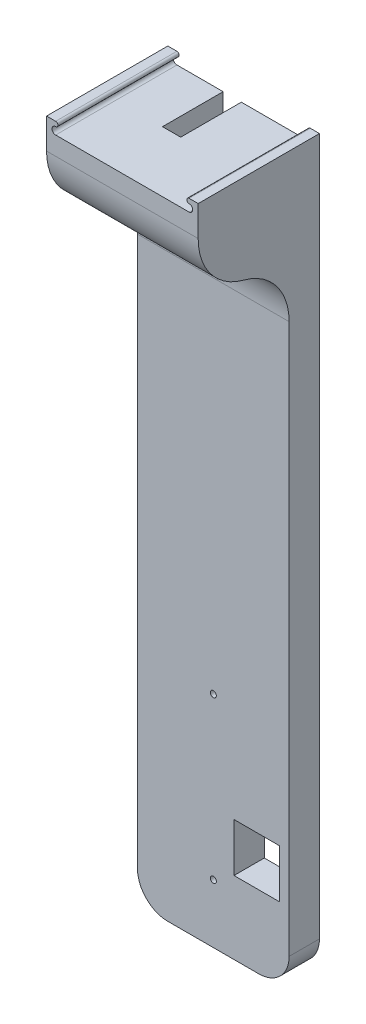
SolidWorks part; units mm, degrees
ref_plane "Přední rovina" through (0, 0, 0) normal (0, 0, 1) x (1, 0, 0)
ref_plane "Horní rovina" through (0, 0, 0) normal (0, 1, 0) x (1, 0, 0)
ref_plane "Pravá rovina" through (0, 0, 0) normal (1, 0, 0) x (0, 0, -1)
sketch "Skica1" plane through (0, 0, 0) normal (0, 0, 1) x (1, 0, 0)
  line L1 (0, 0) -> (25, 0)
  line L2 (0, 0) -> (0, 120)
  line L3 (0, 120) -> (25, 120)
  line L4 (25, 0) -> (25, 120)
  dimension "D1" = 120
  dimension "D2" = 25
extrude "Přidat vysunutím1" add sketch "Skica1" along normal blind 5
sketch "Skica2" plane through (0, 0, 0) normal (0, 0, -1) x (-1, 0, 0)
  line L0 (0, 120) -> (0, 0) construction
  line L1 (-25, 120) -> (0, 120)
  line L2 (-25, 120) -> (-25, 105)
  line L3 (-25, 105) -> (0, 105)
  line L4 (0, 120) -> (0, 105)
  dimension "D1" = 15
extrude "Přidat vysunutím2" add sketch "Skica2" against normal blind 20
fillet "Zaoblit5" radius 5 1 edges at (25, 0, 2.5)
fillet "Zaoblit6" radius 5 1 edges at (0, 0, 2.5)
sketch "Skica3" plane through (0, 0, 20) normal (0, 0, 1) x (1, 0, 0)
  line L0 (1.5, 118.04) -> (23.5, 118.04)
  line L1 (0, 120) -> (25, 120) construction
  line L4 (1.5, 120) -> (23.5, 120)
  line L5 (0, 105) -> (0, 120) construction
  line L6 (25, 120) -> (25, 105) construction
  arc A0 (23.5, 118.04) -> (23.5, 119.24) centre (23.5, 118.64) ccw
  arc A1 (23.5, 119.24) -> (23.5, 120) centre (23.5, 119.62) cw
  arc A2 (1.5, 118.04) -> (1.5, 119.24) centre (1.5, 118.64) cw
  arc A3 (1.5, 119.24) -> (1.5, 120) centre (1.5, 119.62) ccw
  dimension "D1" = 0.6
  dimension "D2" = 0.6
  dimension "D3" = 0.38
  dimension "D4" = 0.38
  dimension "D5" = 1.5
  dimension "D6" = 1.5
  dimension "D7" = 1.96
extrude "Odebrat vysunutím2" cut sketch "Skica3" against normal blind 20
fillet "Zaoblit7" radius 10 1 edges at (12.5, 105, 20)
fillet "Zaoblit8" radius 10 1 edges at (12.5, 105, 5)
sketch "Skica4" plane through (0, 118.04, 0) normal (0, 1, 0) x (1, 0, 0)
  line L0 (1.5, 0) -> (23.5, 0) construction
  line L1 (9.12, 0) -> (12.12, 0)
  line L2 (9.12, 0) -> (9.12, -10)
  line L3 (9.12, -10) -> (12.12, -10)
  line L4 (12.12, 0) -> (12.12, -10)
  line L5 (23.12, 0) -> (23.12, -20) construction
  dimension "D1" = 0
  dimension "D2" = 10
  dimension "D3" = 3
  dimension "D4" = 11
extrude "Odebrat vysunutím3" cut sketch "Skica4" against normal blind 3
sketch "Skica5" plane through (0, 0, 0) normal (0, 0, 1) x (1, 0, 0)
  line L0 (9, 21) -> (16, 21)
  line L1 (16, 21) -> (14, 43)
  line L3 (11, 43) -> (9, 21)
  line L4 (11, 43) -> (14, 43)
  line L5 (9, 21) -> (10.5, 5)
  line L6 (10.5, 5) -> (14.5, 5)
  line L7 (14.5, 5) -> (16, 21)
  line L9 (5, 0) -> (20, 0) construction
  line L10 (5.5, 24) -> (19.5, 24)
  line L11 (5.5, 24) -> (5.5, 20)
  line L12 (5.5, 20) -> (19.5, 20)
  line L13 (19.5, 24) -> (19.5, 20)
  arc A0 (5.5, 24) -> (5.5, 20) centre (5.5, 22) ccw
  arc A1 (19.5, 24) -> (19.5, 20) centre (19.5, 22) cw
  point P2 (12.5, 43)
  point P5 (12.5, 21)
  point P6 (12.5, 5)
  point P11 (12.5, 0)
  point P16 (12.5, 24)
  dimension "D1" = 7
  dimension "D2" = 3
  dimension "D3" = 22
  dimension "D4" = 16
  dimension "D5" = 5
  dimension "D6" = 4
  dimension "D7" = 19
  dimension "D8" = 14
  dimension "D9" = 4
extrude "Odebrat vysunutím4" cut sketch "Skica5" along normal blind 2 contours L3 L10 L1 L4 | L11 A0 | L11 L12 L5 L3 L10 | L10 L3 L0 L1 | L5 L12 L7 L0 | L13 L10 L1 L7 L12 | A1 L13 | L12 L5 L6 L7
sketch "Skica7" plane through (0, 0, 2) normal (0, 0, -1) x (-1, 0, 0)
  line L0 (-11, 43) -> (-14, 43) construction
  line L1 (-21.5, 22) -> (-3.5, 22) construction
  circle A0 centre (-12.5, 36.2) radius 0.5
  circle A1 centre (-12.5, 9.7) radius 0.5
  arc A2 (-19.5, 24) -> (-19.5, 20) centre (-19.5, 22) ccw construction
  arc A3 (-5.5, 20) -> (-5.5, 24) centre (-5.5, 22) ccw construction
  point P9 (-12.5, 43)
  dimension "D1" = 1
  dimension "D2" = 1
  dimension "D4" = 12.3
  dimension "D3" = 14.2
extrude "Odebrat vysunutím5" cut sketch "Skica7" along normal offset from surface (2.8 mm away) 0.2 from surface at -3 up to face at (12.5, 22.6667, 2) starting at face at (12.5, 33.1998, 5)
sketch "Skica8" plane through (0, 0, 2) normal (0, 0, -1) x (-1, 0, 0)
  line L0 (-12.5, 43) -> (-12.5, 5) construction
  line L1 (-11, 43) -> (-14, 43) construction
  line L2 (-10.5, 5) -> (-14.5, 5) construction
  line L3 (-21.5, 22) -> (-3.5, 22) construction
  circle A0 centre (-12.5, 22) radius 3.75
  arc A1 (-19.5, 24) -> (-19.5, 20) centre (-19.5, 22) ccw construction
  arc A2 (-5.5, 20) -> (-5.5, 24) centre (-5.5, 22) ccw construction
  dimension "D3" = 7.5
  dimension "D1" = 0
  dimension "D2" = 0
extrude "Odebrat vysunutím6" cut sketch "Skica8" against normal blind 2
sketch "Skica9" plane through (0, 0, 0) normal (0, 0, -1) x (-1, 0, 0)
  line L1 (-15.9062, 20) -> (-23.4063, 20)
  line L2 (-15.9062, 20) -> (-15.9062, 12)
  line L3 (-15.9062, 12) -> (-23.4062, 12)
  line L4 (-23.4063, 20) -> (-23.4062, 12)
  dimension "D1" = 7.5
  dimension "D2" = 8
extrude "Odebrat vysunutím7" cut sketch "Skica9" against normal through all
